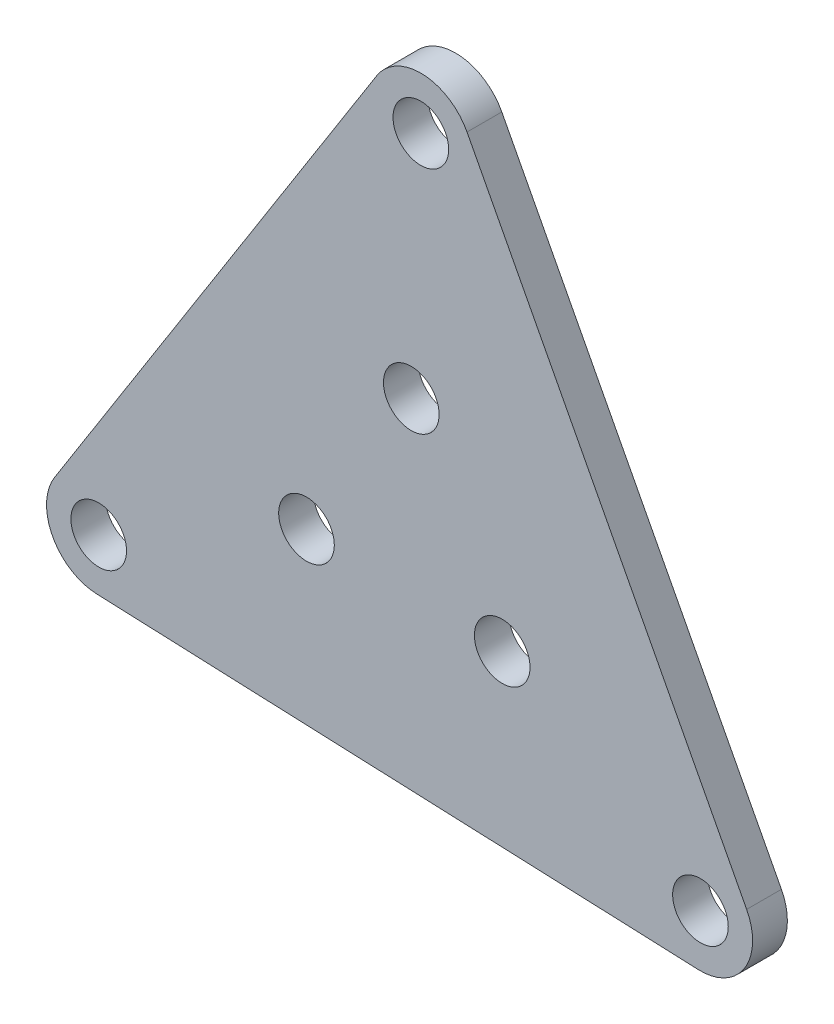
SolidWorks part; units mm, degrees
material "Thornel Mat VMA"
ref_plane "Front Plane" through (0, 0, 0) normal (0, 0, 1) x (1, 0, 0)
ref_plane "Top Plane" through (0, 0, 0) normal (0, 1, 0) x (1, 0, 0)
ref_plane "Right Plane" through (0, 0, 0) normal (1, 0, 0) x (0, 0, -1)
sketch "Sketch1" plane through (0, 0, 0) normal (0, 0, 1) x (1, 0, 0)
  line L3 (-17.8358, -12.2835) -> (16.7764, -13.6949)
  line L4 (19.5557, -9.3045) -> (3.4719, 21.3763)
  line L5 (-1.7199, 21.588) -> (-20.2484, -7.6813)
  line L6 (-17.8358, -12.2835) -> (16.7764, -13.6949)
  line L7 (19.5557, -9.3045) -> (3.4719, 21.3763)
  line L8 (-1.7199, 21.588) -> (-20.2484, -7.6813)
  line L11 (0.2651, 6.5) -> (-5.7617, -3.0204) construction
  line L12 (-5.7617, -3.0204) -> (5.4966, -3.4796) construction
  line L13 (5.4966, -3.4796) -> (0.2651, 6.5) construction
  circle A0 centre (16.8987, -10.6974) radius 1.6 construction
  circle A1 centre (-17.7136, -9.286) radius 1.6 construction
  circle A2 centre (0.8149, 19.9834) radius 1.6 construction
  arc A3 (16.7764, -13.6949) -> (19.5557, -9.3045) centre (16.8987, -10.6974) ccw
  arc A4 (3.4719, 21.3763) -> (-1.7199, 21.588) centre (0.8149, 19.9834) ccw
  arc A5 (-20.2484, -7.6813) -> (-17.8358, -12.2835) centre (-17.7136, -9.286) ccw
  arc A6 (16.7764, -13.6949) -> (19.5557, -9.3045) centre (16.8987, -10.6974) ccw
  arc A7 (3.4719, 21.3763) -> (-1.7199, 21.588) centre (0.8149, 19.9834) ccw
  arc A8 (-20.2484, -7.6813) -> (-17.8358, -12.2835) centre (-17.7136, -9.286) ccw
  circle A9 centre (16.8987, -10.6974) radius 1.6
  circle A10 centre (-17.7136, -9.286) radius 1.6
  circle A11 centre (0.8149, 19.9834) radius 1.6
  circle A16 centre (0, 0) radius 3.2527 construction
  circle A17 centre (0, 0) radius 9 construction
  circle A18 centre (0.2651, 6.5) radius 1.6
  circle A19 centre (-5.7617, -3.0204) radius 1.6
  circle A20 centre (5.4966, -3.4796) radius 1.6
  dimension "D2" = 18
  dimension "D3" = 3.2
  dimension "D4" = 6.5
  dimension "D1" = 0
extrude "Boss-Extrude1" add sketch "Sketch1" along normal blind 2
